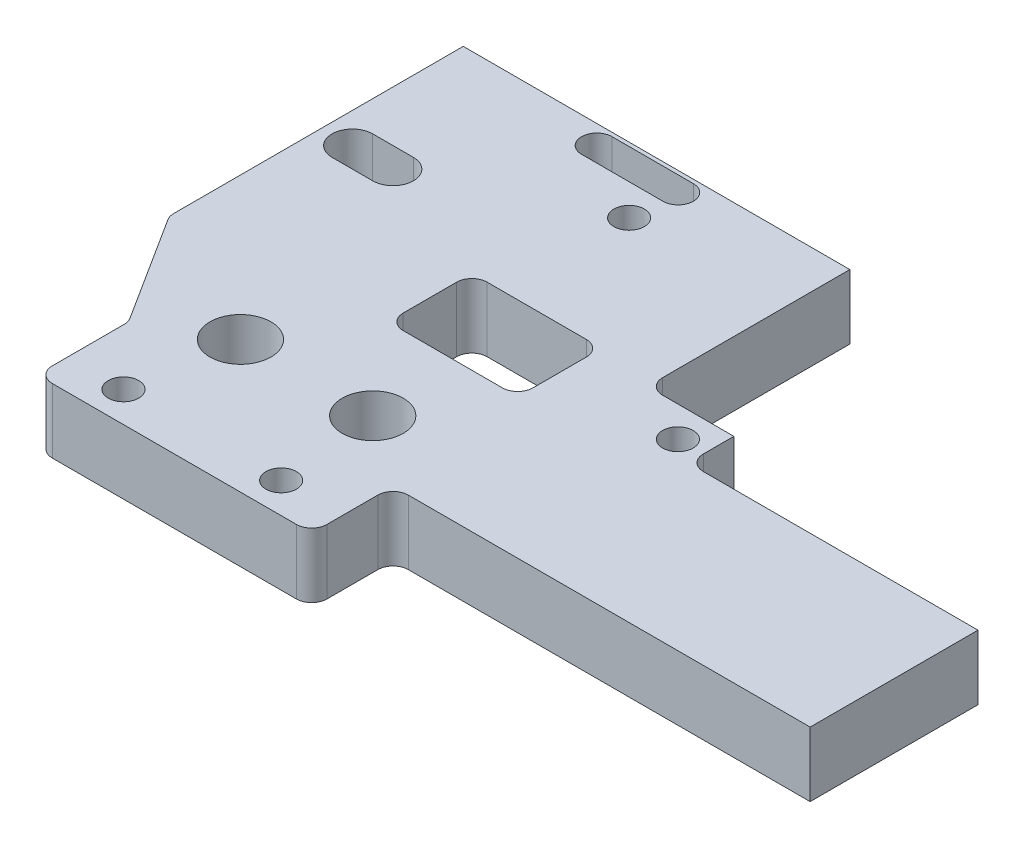
SolidWorks part; units mm, degrees
material "1060 Alloy"
ref_plane "Front Plane" through (0, 0, 0) normal (0, 0, 1) x (1, 0, 0)
ref_plane "Top Plane" through (0, 0, 0) normal (0, 1, 0) x (1, 0, 0)
ref_plane "Right Plane" through (0, 0, 0) normal (1, 0, 0) x (0, 0, -1)
sketch "Sketch1" plane through (0, 0, 0) normal (0, 1, 0) x (1, 0, 0)
  line L0 (48, 228) -> (48, 71.7384) construction
  line L2 (0, 20) -> (0, 104)
  line L4 (96, 20) -> (96, 104)
  line L5 (33.5, 114) -> (26, 107)
  line L6 (26, 107) -> (26, 93)
  line L7 (26, 93) -> (14, 93)
  line L8 (14, 93) -> (12, 104)
  line L9 (12, 104) -> (0, 104)
  line L10 (62.5, 114) -> (70, 107)
  line L11 (70, 107) -> (70, 93)
  line L12 (70, 93) -> (82, 93)
  line L13 (82, 93) -> (84, 104)
  line L14 (84, 104) -> (96, 104)
  line L15 (33.5, 114) -> (62.5, 114)
  line L16 (0, 20) -> (7, 9)
  line L17 (7, 9) -> (7, 0)
  line L18 (89, 9) -> (89, 0)
  line L19 (96, 20) -> (89, 9)
  line L20 (7, 0) -> (34, 0)
  line L21 (34, 0) -> (34, 8)
  line L22 (34, 8) -> (62, 8)
  line L23 (89, 0) -> (62, 0)
  line L24 (62, 0) -> (62, 8)
  line L25 (76.25, 21.75) -> (63.5, 21.75)
  line L26 (19.75, 30) -> (32.5, 30)
  line L27 (19.75, 30) -> (19.75, 21.75)
  line L28 (19.75, 21.75) -> (32.5, 21.75)
  line L29 (32.5, 30) -> (32.5, 21.75)
  line L30 (63.5, 30) -> (63.5, 21.75)
  line L31 (76.25, 30) -> (63.5, 30)
  line L32 (76.25, 30) -> (76.25, 21.75)
  line L33 (0, 53.875) -> (96, 53.875) construction
  line L34 (76.25, 77.75) -> (76.25, 86)
  line L35 (76.25, 77.75) -> (63.5, 77.75)
  line L36 (63.5, 77.75) -> (63.5, 86)
  line L37 (76.25, 86) -> (63.5, 86)
  line L38 (19.75, 86) -> (32.5, 86)
  line L39 (32.5, 77.75) -> (32.5, 86)
  line L40 (19.75, 77.75) -> (32.5, 77.75)
  line L41 (19.75, 77.75) -> (19.75, 86)
  line L42 (3, 75) -> (7, 75)
  line L43 (3, 71) -> (7, 71)
  line L44 (93, 75) -> (89, 75)
  line L45 (93, 71) -> (89, 71)
  line L46 (0, 54) -> (96, 54) construction
  line L47 (93, 37) -> (89, 37)
  line L48 (93, 33) -> (89, 33)
  line L49 (3, 33) -> (7, 33)
  line L50 (3, 37) -> (7, 37)
  line L51 (15, 48.5252) -> (23, 48.5252)
  line L52 (23, 45.5252) -> (15, 45.5252)
  line L53 (81, 48.5252) -> (73, 48.5252)
  line L54 (73, 45.5252) -> (81, 45.5252)
  line L55 (16.5, 67.75) -> (16.5, 57.75)
  line L56 (19.5, 67.75) -> (19.5, 57.75)
  line L57 (76.5, 67.75) -> (76.5, 57.75)
  line L58 (79.5, 67.75) -> (79.5, 57.75)
  line L59 (46.5, 29) -> (38, 29)
  line L60 (38, 29) -> (38, 71)
  line L61 (38, 71) -> (46.5, 71)
  line L62 (46.5, 29) -> (46.5, 26)
  line L63 (18.7278, 50) -> (57.2722, 50) construction
  line L64 (46.5, 71) -> (46.5, 74)
  line L65 (49.5, 29) -> (49.5, 26)
  line L66 (49.5, 29) -> (58, 29)
  line L67 (58, 29) -> (58, 71)
  line L68 (49.5, 71) -> (49.5, 74)
  line L69 (58, 71) -> (49.5, 71)
  line L70 (35.5, 106.5) -> (60.5, 89) construction
  circle A0 centre (12.5, 3) radius 1.5
  circle A1 centre (28, 3) radius 1.5
  circle A2 centre (68, 3) radius 1.5
  circle A3 centre (83.5, 3) radius 1.5
  circle A4 centre (14, 13) radius 3
  circle A5 centre (27, 13) radius 3
  circle A6 centre (69, 13) radius 3
  circle A7 centre (82, 13) radius 3
  arc A8 (3, 75) -> (3, 71) centre (3, 73) ccw
  arc A10 (7, 71) -> (7, 75) centre (7, 73) ccw
  arc A11 (89, 71) -> (89, 75) centre (89, 73) cw
  arc A12 (93, 75) -> (93, 71) centre (93, 73) cw
  arc A13 (93, 33) -> (93, 37) centre (93, 35) ccw
  arc A14 (89, 37) -> (89, 33) centre (89, 35) ccw
  arc A15 (7, 37) -> (7, 33) centre (7, 35) cw
  arc A16 (3, 33) -> (3, 37) centre (3, 35) cw
  circle A17 centre (22.75, 42.455) radius 1.5
  arc A18 (23, 45.5252) -> (23, 48.5252) centre (23, 47.0252) ccw
  arc A19 (15, 48.5252) -> (15, 45.5252) centre (15, 47.0252) ccw
  circle A20 centre (22.75, 51.7511) radius 1.5
  circle A21 centre (73.25, 42.455) radius 1.5
  arc A22 (73, 45.5252) -> (73, 48.5252) centre (73, 47.0252) cw
  arc A23 (81, 48.5252) -> (81, 45.5252) centre (81, 47.0252) cw
  circle A24 centre (73.25, 51.7511) radius 1.5
  circle A25 centre (18, 72.75) radius 1.5
  arc A26 (19.5, 67.75) -> (16.5, 67.75) centre (18, 67.75) ccw
  arc A27 (16.5, 57.75) -> (19.5, 57.75) centre (18, 57.75) ccw
  circle A28 centre (28, 65.75) radius 1.5
  circle A29 centre (68, 65.75) radius 1.5
  circle A30 centre (78, 72.75) radius 1.5
  arc A31 (79.5, 57.75) -> (76.5, 57.75) centre (78, 57.75) cw
  arc A32 (76.5, 67.75) -> (79.5, 67.75) centre (78, 67.75) cw
  circle A33 centre (36.5, 76.75) radius 2
  circle A34 centre (59.5, 76.75) radius 2
  circle A35 centre (35.5, 89) radius 1.5
  circle A36 centre (35.5, 106.5) radius 1.5
  circle A37 centre (60.5, 89) radius 1.5
  circle A38 centre (60.5, 106.5) radius 1.5
  arc A39 (46.5, 26) -> (49.5, 26) centre (48, 26) ccw
  arc A40 (46.5, 74) -> (49.5, 74) centre (48, 74) cw
  circle A41 centre (44, 26) radius 1.5
  circle A42 centre (52, 26) radius 1.5
  circle A43 centre (52, 74) radius 1.5
  circle A44 centre (44, 74) radius 1.5
  circle A45 centre (48, 97.75) radius 2
  point P8 (48, 149.8692)
  point P28 (48, 8)
  point P150 (38, 50)
  dimension "D13" = 3
  dimension "D14" = 3
  dimension "D15" = 5.5
  dimension "D16" = 6
  dimension "D17" = 3
  dimension "D18" = 6
  dimension "D19" = 13
  dimension "D20" = 14
  dimension "D21" = 13
  dimension "D27" = 4
  dimension "D28" = 4
  dimension "D29" = 4
  dimension "D30" = 31
  dimension "D32" = 3
  dimension "D34" = 3
  dimension "D35" = 3
  dimension "D36" = 22.75
  dimension "D37" = 3
  dimension "D39" = 15
  dimension "D40" = 3
  dimension "D41" = 11
  dimension "D42" = 5
  dimension "D43" = 5
  dimension "D44" = 10
  dimension "D45" = 3
  dimension "D46" = 10
  dimension "D47" = 7
  dimension "D48" = 4
  dimension "D49" = 4
  dimension "D50" = 1
  dimension "D51" = 3
  dimension "D52" = 3
  dimension "D53" = 3
  dimension "D54" = 17.5
  dimension "D55" = 21
  dimension "D60" = 3
  dimension "D61" = 3
  dimension "D58" = 3
  dimension "D62" = 4
  dimension "D63" = 4
  dimension "D1" = 10
  dimension "D2" = 96
  dimension "D3" = 12
  dimension "D4" = 21
  dimension "D5" = 7
  dimension "D6" = 7.5
  dimension "D7" = 12
  dimension "D8" = 2
  dimension "D9" = 27
  dimension "D10" = 7
  dimension "D11" = 9
  dimension "D12" = 8
  dimension "D22" = 8.25
  dimension "D23" = 12.75
  dimension "D24" = 21.75
  dimension "D25" = 19.75
  dimension "D26" = 23.875
  dimension "D31" = 114
  dimension "D33" = 17
  dimension "D38" = 8
  dimension "D56" = 42
  dimension "D57" = 38
  dimension "D59" = 1.5
extrude "Boss-Extrude1" add sketch "Sketch1" along normal blind 6.35
fillet "Fillet1" radius 1.5 42 edges at (38, 3.175, -29) (58, 3.175, -71) (63.5, 3.175, -30) (63.5, 3.175, -86) (32.5, 3.175, -86) (32.5, 3.175, -30) (76.25, 3.175, -30) (76.25, 3.175, -86) (19.75, 3.175, -77.75) (63.5, 3.175, -77.75) (63.5, 3.175, -21.75) (19.75, 3.175, -21.75) (32.5, 3.175, -21.75) (32.5, 3.175, -77.75) (76.25, 3.175, -77.75) (58, 3.175, -29) (76.25, 3.175, -21.75) (0, 3.175, -104) (12, 3.175, -104) (14, 3.175, -93) (26, 3.175, -93) (26, 3.175, -107) (33.5, 3.175, -114) (62.5, 3.175, -114) (70, 3.175, -107) (70, 3.175, -93) (82, 3.175, -93) (84, 3.175, -104) (96, 3.175, -104) (96, 3.175, -20) (89, 3.175, -9) (89, 3.175, 0) (62, 3.175, -8) (62, 3.175, 0) (19.75, 3.175, -86) (38, 3.175, -71) (19.75, 3.175, -30) (34, 3.175, -8) (34, 3.175, 0) (0, 3.175, -20) (7, 3.175, -9) (7, 3.175, 0)
ref_plane "Plane1" through (48, 0, 0) normal (1, 0, 0) x (0, 0, -1)
sketch "Sketch3" plane through (48, 0, 0) normal (1, 0, 0) x (0, 0, -1)
  line L1 (-6.4167, 7.5787) -> (123.2615, 7.5787)
  line L2 (-6.4167, 7.5787) -> (-6.4167, -5.6973)
  line L3 (-6.4167, -5.6973) -> (123.2615, -5.6973)
  line L4 (123.2615, 7.5787) -> (123.2615, -5.6973)
extrude "Cut-Extrude1" cut sketch "Sketch3" along normal blind 56
sketch "Sketch4" plane through (48, 0, 0) normal (1, 0, 0) x (0, 0, -1)
  line L4 (114, 0) -> (114, 6.35)
  line L5 (114, 6.35) -> (99.75, 6.35)
  line L6 (99.75, 6.35) -> (99.75, 0)
  line L7 (99.75, 0) -> (114, 0)
  line L8 (114, 0) -> (114, 6.35)
  line L9 (114, 6.35) -> (99.75, 6.35)
  line L10 (99.75, 6.35) -> (99.75, 0)
  line L11 (99.75, 0) -> (114, 0)
  line L12 (75.5, 0) -> (95.75, 0)
  line L13 (95.75, 0) -> (95.75, 6.35)
  line L14 (95.75, 6.35) -> (75.5, 6.35)
  line L15 (75.5, 6.35) -> (75.5, 0)
  line L16 (75.5, 0) -> (95.75, 0)
  line L17 (95.75, 0) -> (95.75, 6.35)
  line L18 (95.75, 6.35) -> (75.5, 6.35)
  line L19 (75.5, 6.35) -> (75.5, 0)
  line L28 (8, 6.35) -> (8, 0)
  line L29 (8, 0) -> (24.5, 0)
  line L30 (24.5, 0) -> (24.5, 6.35)
  line L31 (24.5, 6.35) -> (8, 6.35)
  line L32 (8, 6.35) -> (8, 0)
  line L33 (8, 0) -> (24.5, 0)
  line L34 (24.5, 0) -> (24.5, 6.35)
  line L35 (24.5, 6.35) -> (8, 6.35)
  dimension "D1" = 0
  dimension "D2" = 0
  dimension "D4" = 0
extrude "Boss-Extrude2" add sketch "Sketch4" along normal blind 25
mirror "Mirror1" about plane through (73, 0, 0) normal (1, 0, 0) of bodies 103
ref_plane "Plane2" through (75, 0, 0) normal (1, 0, 0) x (0, 0, -1)
sketch "Sketch5" plane through (75, 0, 0) normal (1, 0, 0) x (0, 0, -1)
  line L1 (-24.6869, 38.3801) -> (134.1511, 38.3801)
  line L2 (-24.6869, 38.3801) -> (-24.6869, -30.8448)
  line L3 (-24.6869, -30.8448) -> (134.1511, -30.8448)
  line L4 (134.1511, 38.3801) -> (134.1511, -30.8448)
extrude "Cut-Extrude2" cut sketch "Sketch5" along normal blind 86
sketch "Sketch6" plane through (38, 0, 0) normal (1, 0, 0) x (0, 0, -1)
  line L0 (48.9, 6.35) -> (48.9, 0)
  line L1 (30.5, 6.35) -> (30.5, 0) construction
  line L3 (49, 0) -> (49, 6.35)
  line L4 (69.5, 0) -> (30.5, 0) construction
  line L5 (69.5, 6.35) -> (30.5, 6.35) construction
  line L6 (48.9, 6.35) -> (49, 6.35)
  line L7 (48.9, 0) -> (49, 0)
  dimension "D1" = 18.4
  dimension "D2" = 0.1
extrude "Cut-Extrude3" cut sketch "Sketch6" against normal blind 49 and the other way blind 10
ref_plane "Plane3" through (0, 0, -48.91) normal (0, 0, -1) x (-1, 0, 0)
sketch "Sketch7" plane through (0, 0, -48.91) normal (0, 0, -1) x (-1, 0, 0)
  line L1 (-82.8539, 16.7318) -> (5.6106, 16.7318)
  line L2 (-82.8539, 16.7318) -> (-82.8539, -6.3838)
  line L3 (-82.8539, -6.3838) -> (5.6106, -6.3838)
  line L4 (5.6106, 16.7318) -> (5.6106, -6.3838)
extrude "Cut-Extrude4" cut sketch "Sketch7" along normal blind 84 contours L2 L3 L4 L1
